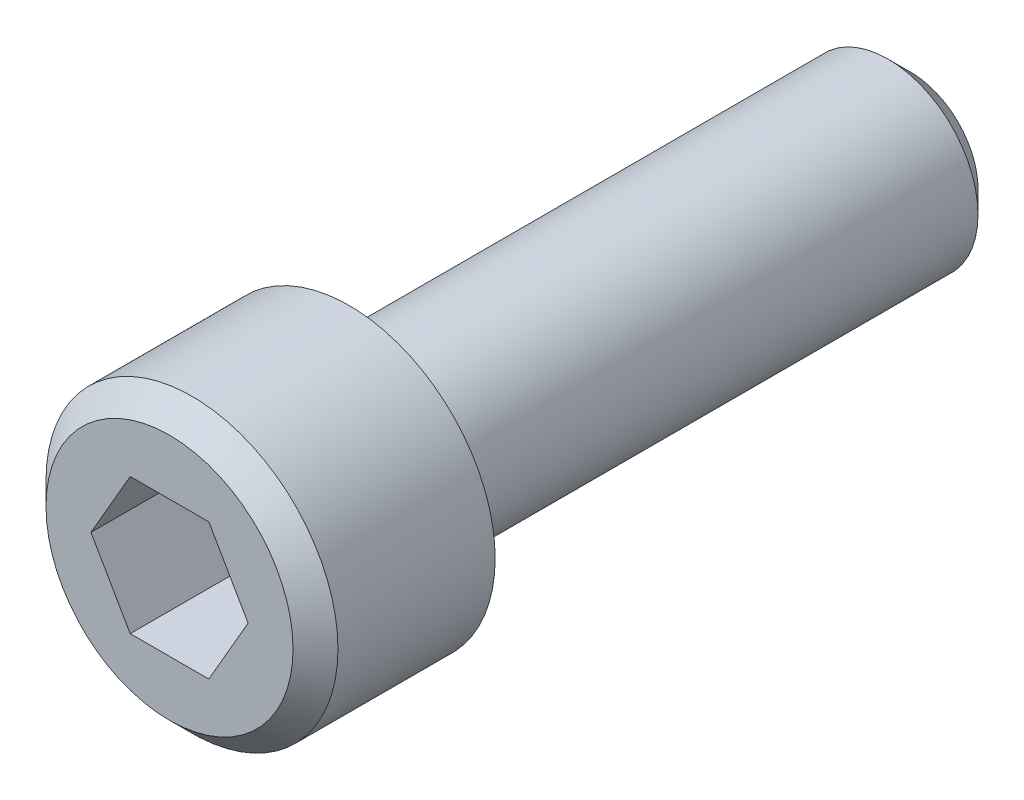
SolidWorks part; units mm, degrees
ref_plane "Alzado" through (0, 0, 0) normal (0, 0, 1) x (1, 0, 0)
ref_plane "Planta" through (0, 0, 0) normal (0, 1, 0) x (1, 0, 0)
ref_plane "Vista lateral" through (0, 0, 0) normal (1, 0, 0) x (0, 0, -1)
sketch "Croquis1" plane through (0, 0, 0) normal (0, 0, 1) x (1, 0, 0)
  circle A0 centre (0, 0) radius 6.5
  dimension "D1" = 13
extrude "Saliente-Extruir1" add sketch "Croquis1" along normal blind 8
sketch "Croquis2" plane through (0, 0, 0) normal (0, 0, -1) x (-1, 0, 0)
  circle A0 centre (0, 0) radius 4
  dimension "D1" = 8
extrude "Saliente-Extruir2" add sketch "Croquis2" along normal blind 25
chamfer "Chaflán1" distance 1 angle 45 2 edges at (6.5, 0, 8) (-4, 0, -25)
sketch "Croquis3" plane through (0, 0, 8) normal (0, 0, 1) x (1, 0, 0)
  line L1 (3.5, 0) -> (1.75, 3.0311)
  line L2 (1.75, 3.0311) -> (-1.75, 3.0311)
  line L3 (-1.75, 3.0311) -> (-3.5, 0)
  line L4 (-3.5, 0) -> (-1.75, -3.0311)
  line L5 (-1.75, -3.0311) -> (1.75, -3.0311)
  line L6 (1.75, -3.0311) -> (3.5, 0)
  circle A0 centre (0, 0) radius 3.0311 construction
  dimension "D1" = 7
extrude "Cortar-Extruir1" cut sketch "Croquis3" against normal blind 6
